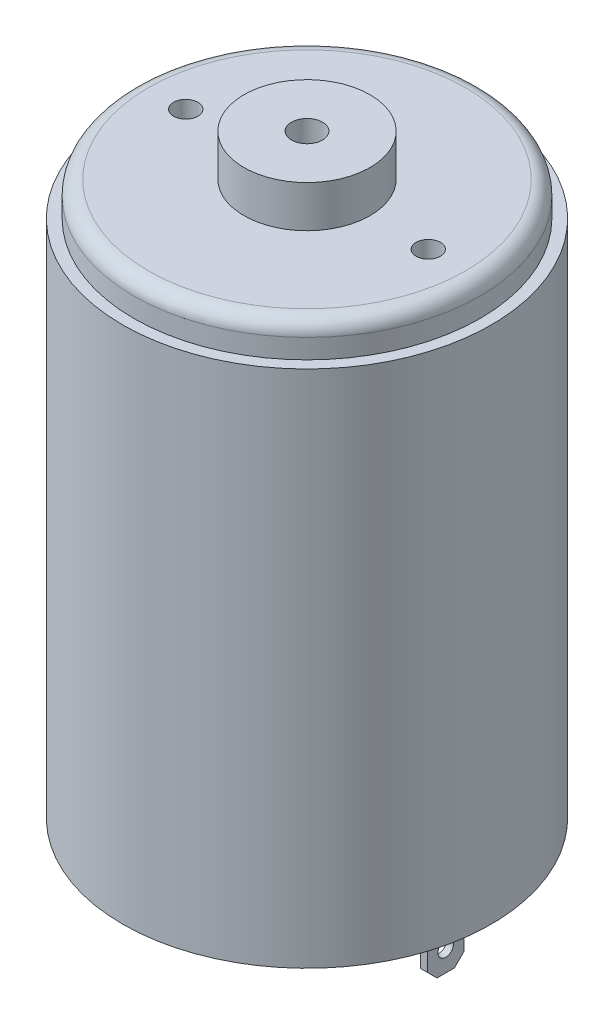
SolidWorks part; units mm, degrees
ref_plane "Plan de face" through (0, 0, 0) normal (0, 0, 1) x (1, 0, 0)
ref_plane "Plan de dessus" through (0, 0, 0) normal (0, 1, 0) x (1, 0, 0)
ref_plane "Plan de droite" through (0, 0, 0) normal (1, 0, 0) x (0, 0, -1)
sketch "Esquisse1" plane through (0, 0, 0) normal (0, 0, 1) x (1, 0, 0)
  line L0 (0, 0) -> (0, 85) construction
  line L1 (0, 0) -> (-1.6, 0)
  line L2 (-1.6, 0) -> (-1.6, 2.6)
  line L3 (-1.6, 2.6) -> (-5.075, 2.6)
  line L4 (-5.075, 2.6) -> (-5.075, 4.5)
  line L5 (-5.075, 4.5) -> (-19, 4.5)
  line L6 (-19, 4.5) -> (-19, 58)
  line L7 (-19, 58) -> (-17.85, 58)
  line L8 (-17.85, 58) -> (-17.85, 60)
  line L9 (-16.35, 61.5) -> (-6.5, 61.5)
  line L10 (-6.5, 61.5) -> (-6.5, 65.8)
  line L11 (-6.5, 65.8) -> (-1.6, 65.8)
  line L12 (-1.6, 65.8) -> (-1.6, 85)
  line L13 (-1.6, 85) -> (0, 85)
  line L14 (0, 0) -> (0, 85)
  arc A0 (-17.85, 60) -> (-16.35, 61.5) centre (-16.35, 60) cw
  dimension "D13" = 1.5
  dimension "D1" = 3.2
  dimension "D2" = 2.6
  dimension "D3" = 10.15
  dimension "D4" = 4.5
  dimension "D5" = 38
  dimension "D6" = 53.5
  dimension "D7" = 35.7
  dimension "D8" = 57
  dimension "D9" = 13
  dimension "D10" = 4.3
  dimension "D11" = 3.2
  dimension "D12" = 85
revolve "Révolution1" add sketch "Esquisse1" angle 360 about L0
sketch "Esquisse2" plane through (0, 85, 0) normal (0, 1, 0) x (1, 0, 0)
  line L0 (-1.1619, -1.1) -> (1.1619, -1.1)
  circle A1 centre (0, 0) radius 1.6
  arc A2 (-1.1619, -1.1) -> (1.1619, -1.1) centre (0, 0) ccw
  dimension "D2" = 1.1
  dimension "D1" = 0
extrude "Enlèv. mat.-Extru.1" cut sketch "Esquisse2" against normal blind 15
hole_wizard "Trou taraudé M31" positions "Esquisse4" profile "Esquisse3" tap size "M3" standard "ISO"
sketch "Esquisse4" plane through (0, 61.5, 0) normal (0, 1, 0) x (-1, 0, 0)
  point P0 (12.5, 0)
  point P1 (-12.5, 0)
  dimension "D1" = 25
  dimension "D2" = 12.5
sketch "Esquisse3" plane through (-12.5, 61.5, 0) normal (1, 0, 0) x (0, 0, 1)
  line L0 (0, 0) -> (0, 9.2511)
  line L1 (0, 9.2511) -> (1.25, 8.5)
  line L2 (1.25, 8.5) -> (1.25, 0)
  line L5 (1.25, 0) -> (0, 0)
  line L10 (0, 9.2511) -> (-1.25, 8.5) construction
  line L11 (0, -6.35) -> (0, 107.95) construction
  dimension "Diamètre du trou pour taraudage" = 2.5
  dimension "Profondeur du trou pour taraudage" = 8.5
  dimension "Angle de pointe" = 118
cosmetic thread "Filetage de perçage1" parameters "D1"=6, "D2"=3
cosmetic thread "Filetage de perçage2" parameters "D1"=6, "D2"=3
sketch "Esquisse5" plane through (0, 4.5, 0) normal (0, -1, 0) x (1, 0, 0)
  line L1 (-14.3, 1.9) -> (-13.6, 1.9)
  line L2 (-14.3, 1.9) -> (-14.3, -1.9)
  line L3 (-14.3, -1.9) -> (-13.6, -1.9)
  line L4 (-13.6, 1.9) -> (-13.6, -1.9)
  dimension "D1" = 14.3
  dimension "D2" = 0.7
  dimension "D3" = 3.8
  dimension "D4" = 1.9
extrude "Boss.-Extru.1" add sketch "Esquisse5" along normal blind 6.7
chamfer "Chanfrein1" distance 1 angle 45 2 edges at (-13.95, -2.2, 1.9) (-13.95, -2.2, -1.9)
sketch "Esquisse6" plane through (-14.3, 0, 0) normal (-1, 0, 0) x (0, 0, 1)
  circle A0 centre (0, 0) radius 0.8
  dimension "D1" = 1.6
extrude "Enlèv. mat.-Extru.2" cut sketch "Esquisse6" against normal blind 6.7
pattern_circular "Répétition circulaire1" count 2 over 360 about axis through (0, 0, 0) along (0, 1, 0) of "Enlèv. mat.-Extru.2", "Boss.-Extru.1", "Chanfrein1"
sketch "Esquisse7" plane through (0, 0, 0) normal (0, -1, 0) x (1, 0, 0)
  circle A1 centre (0, 0) radius 1.6
  circle A2 centre (0, 0) radius 1.6
  dimension "D1" = 0
extrude "Enlèv. mat.-Extru.3" cut sketch "Esquisse7" against normal through all
